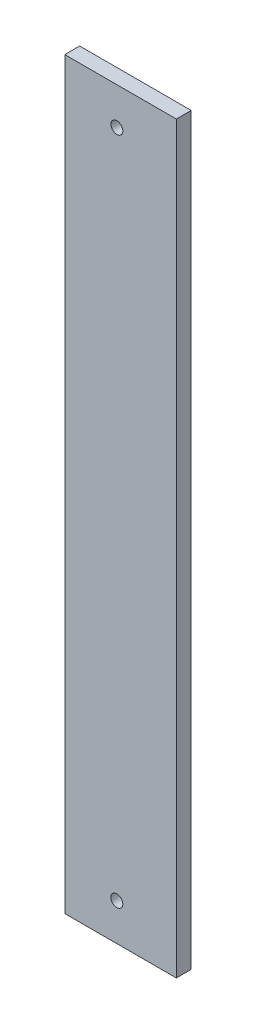
SolidWorks part; units mm, degrees
ref_plane "Front Plane" through (0, 0, 0) normal (0, 0, 1) x (1, 0, 0)
ref_plane "Top Plane" through (0, 0, 0) normal (0, 1, 0) x (1, 0, 0)
ref_plane "Right Plane" through (0, 0, 0) normal (1, 0, 0) x (0, 0, -1)
sketch "Sketch1" plane through (0, 0, 0) normal (0, 0, 1) x (1, 0, 0)
  line L0 (0, 0) -> (75, 0)
  line L1 (75, 0) -> (75, 500)
  line L2 (75, 500) -> (0, 500)
  line L3 (0, 500) -> (0, 0)
  point P3 (35, 25)
  point P6 (35, 475)
  point P7 (0, 0)
  point P8 (0, 0)
  point P10 (40.1685, 468.7575)
  dimension "D1" = 500
  dimension "D2" = 75
  dimension "D3" = 25
  dimension "D4" = 40
  dimension "D5" = 25
extrude "Boss-Extrude1" add sketch "Sketch1" along normal blind 10
sketch "Sketch2" plane through (0, 0, 10) normal (0, 0, 1) x (1, 0, 0)
  line L0 (0, 0) -> (75, 0) construction
  line L1 (75, 500) -> (0, 500) construction
  line L2 (75, 0) -> (75, 500) construction
  point P0 (35, 25)
  point P1 (35, 475)
  point P2 (0, 0)
  point P3 (0, 0)
  dimension "D1" = 25
  dimension "D2" = 25
  dimension "D3" = 40
hole_wizard "Ø8.0mm Dowel Hole1" positions "Sketch2" profile "Sketch3" hole size "Ø8.0" standard "ANSI Metric" end condition through all
sketch "Sketch3" plane through (35, 25, 10) normal (1, 0, 0) x (0, -1, 0)
  line L0 (0, 0) -> (0, 10)
  line L1 (0, 10) -> (4, 10)
  line L2 (4, 10) -> (4, 0)
  line L5 (4, 0) -> (0, 0)
  line L11 (0, -6.35) -> (0, 107.95) construction
  dimension "Thru Hole Dia." = 8
  dimension "Thru Hole Depth" = 10
